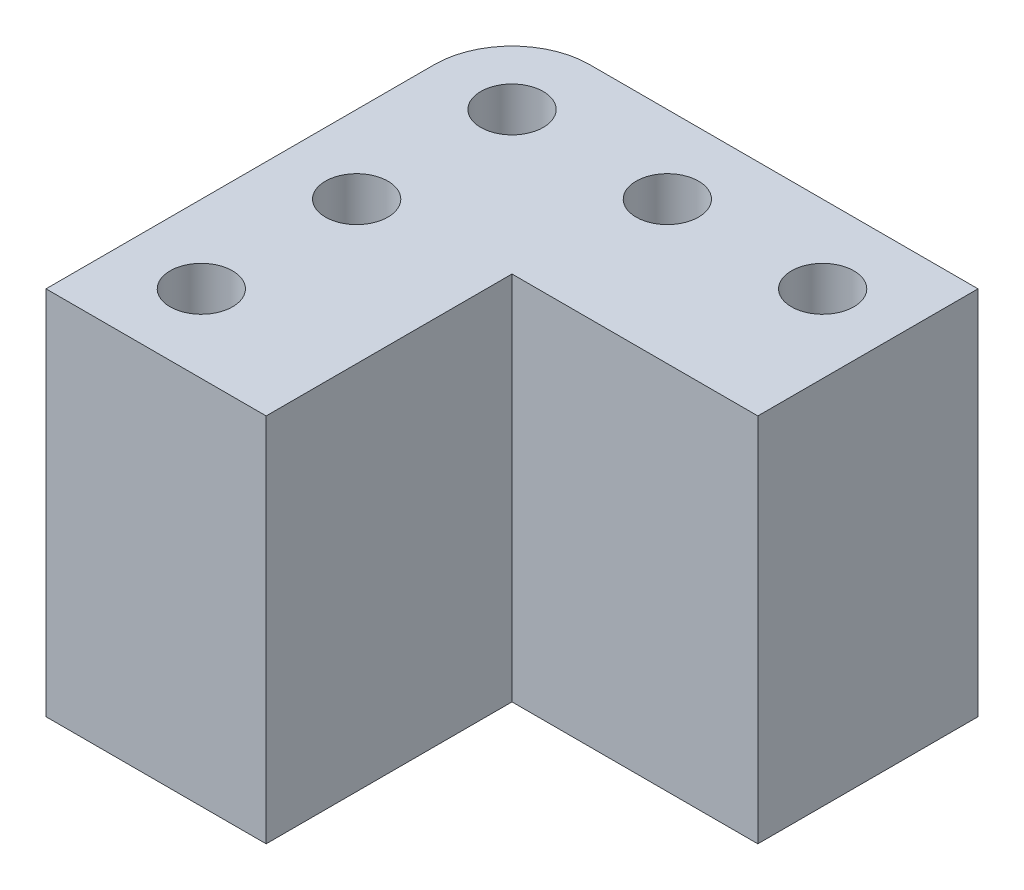
SolidWorks part; units mm, degrees
ref_plane "Front Plane" through (0, 0, 0) normal (0, 0, 1) x (1, 0, 0)
ref_plane "Top Plane" through (0, 0, 0) normal (0, 1, 0) x (1, 0, 0)
ref_plane "Right Plane" through (0, 0, 0) normal (1, 0, 0) x (0, 0, -1)
sketch "Sketch1" plane through (0, 0, 0) normal (0, 1, 0) x (1, 0, 0)
  line L0 (0, 0) -> (38.1, 0)
  line L1 (0, 0) -> (0, -38.1)
  line L2 (0, -38.1) -> (18, -38.1)
  line L3 (18, -38.1) -> (18, -18)
  line L4 (18, -18) -> (38.1, -18)
  line L5 (38.1, -18) -> (38.1, 0)
  point P3 (19.9311, -19.9311)
  dimension "D1" = 38.1
  dimension "D2" = 18
extrude "Boss-Extrude1" add sketch "Sketch1" along normal blind 30.3
sketch "Sketch2" plane through (0, 30.3, 0) normal (0, 1, 0) x (1, 0, 0)
  circle A0 centre (6.35, -6.35) radius 2.5527
  circle A1 centre (19.05, -6.35) radius 2.5527
  circle A2 centre (31.75, -6.35) radius 2.5527
  circle A3 centre (6.35, -19.05) radius 2.5527
  circle A4 centre (6.35, -31.75) radius 2.5527
sketch "Sketch3" plane through (0, 30.3, 0) normal (0, 1, 0) x (1, 0, 0)
  line L0 (0, -6.35) -> (-3.0233, -6.35)
  line L1 (-3.0233, -6.35) -> (-3.0233, 2.9319)
  line L2 (-3.0233, 2.9319) -> (6.35, 2.9319)
  line L3 (6.35, 2.9319) -> (6.35, 0)
  arc A0 (6.35, 0) -> (0, -6.35) centre (6.35, -6.35) ccw
extrude "Cut-Extrude1" cut sketch "Sketch2" against normal through all
extrude "Cut-Extrude2" cut sketch "Sketch3" against normal through all
